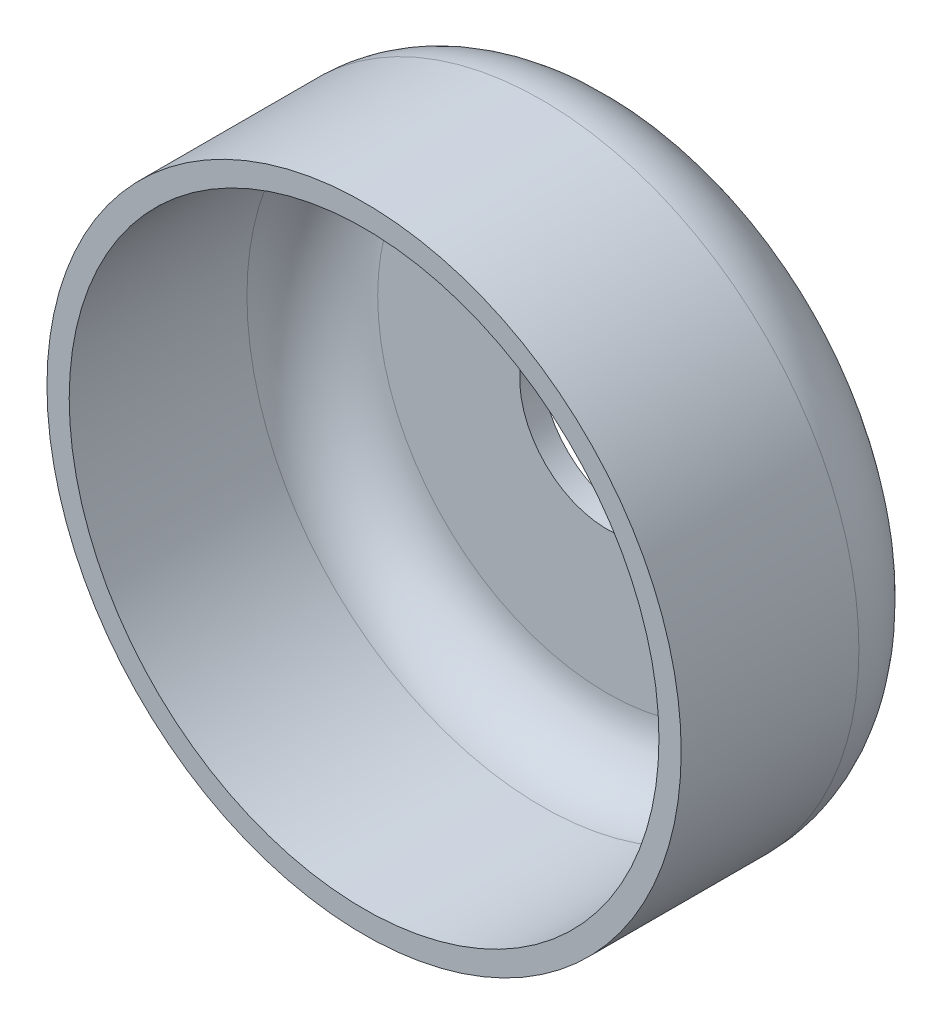
SolidWorks part; units mm, degrees
material "Copper"
ref_plane "Front" through (0, 0, 0) normal (0, 0, 1) x (1, 0, 0)
ref_plane "Top" through (0, 0, 0) normal (0, 1, 0) x (1, 0, 0)
ref_plane "Right" through (0, 0, 0) normal (1, 0, 0) x (0, 0, -1)
sketch "Sketch1" plane through (0, 0, 0) normal (1, 0, 0) x (0, 0, -1)
  line L0 (-11.176, 0) -> (11.176, 0) construction
  line L1 (11.176, 0) -> (11.176, 11.9507) construction
  line L2 (11.176, 11.9507) -> (-11.176, 11.9507) construction
  line L3 (-11.176, 11.9507) -> (-11.176, 11.1125)
  line L4 (-11.176, 11.1125) -> (10.3378, 11.1125) construction
  line L5 (10.3378, 11.1125) -> (10.3378, 0) construction
  line L7 (10.3378, 0) -> (11.176, 0)
  line L8 (-11.176, 11.9507) -> (7.874, 11.9507)
  line L9 (-11.176, 11.1125) -> (7.874, 11.1125)
  line L10 (10.3378, 8.6487) -> (10.3378, 0)
  line L11 (11.176, 8.6487) -> (11.176, 0)
  arc A0 (7.874, 11.1125) -> (10.3378, 8.6487) centre (7.874, 8.6487) cw
  arc A1 (7.874, 11.9507) -> (11.176, 8.6487) centre (7.874, 8.6487) cw
  dimension "Th" = 0.8382
  dimension "Length" = 22.352
  dimension "ID" = 22.225
  dimension "Edge" = 3.302
revolve "Revolve1" add sketch "Sketch1" angle 360 about L0
sketch "Sketch2" plane through (0, 0, 0) normal (0, 1, 0) x (1, 0, 0)
  line L0 (11.9507, -11.176) -> (11.9507, 7.874) construction
  line L1 (-11.9507, -11.176) -> (11.9507, -11.176)
  line L2 (-11.9507, -11.176) -> (-11.9507, 1.176)
  line L3 (-11.9507, 1.176) -> (11.9507, 1.176)
  line L4 (11.9507, -11.176) -> (11.9507, 1.176)
  line L5 (8.6487, 11.176) -> (-8.6487, 11.176) construction
  dimension "D1" = 10
extrude "Cut-Extrude1" cut sketch "Sketch2" against normal through all and the other way through all
sketch "Sketch3" plane through (0, 0, -10.3378) normal (0, 0, 1) x (1, 0, 0)
  circle A0 centre (0, 0) radius 3.3
  dimension "D1" = 6.6
extrude "Cut-Extrude2" cut sketch "Sketch3" against normal through all
